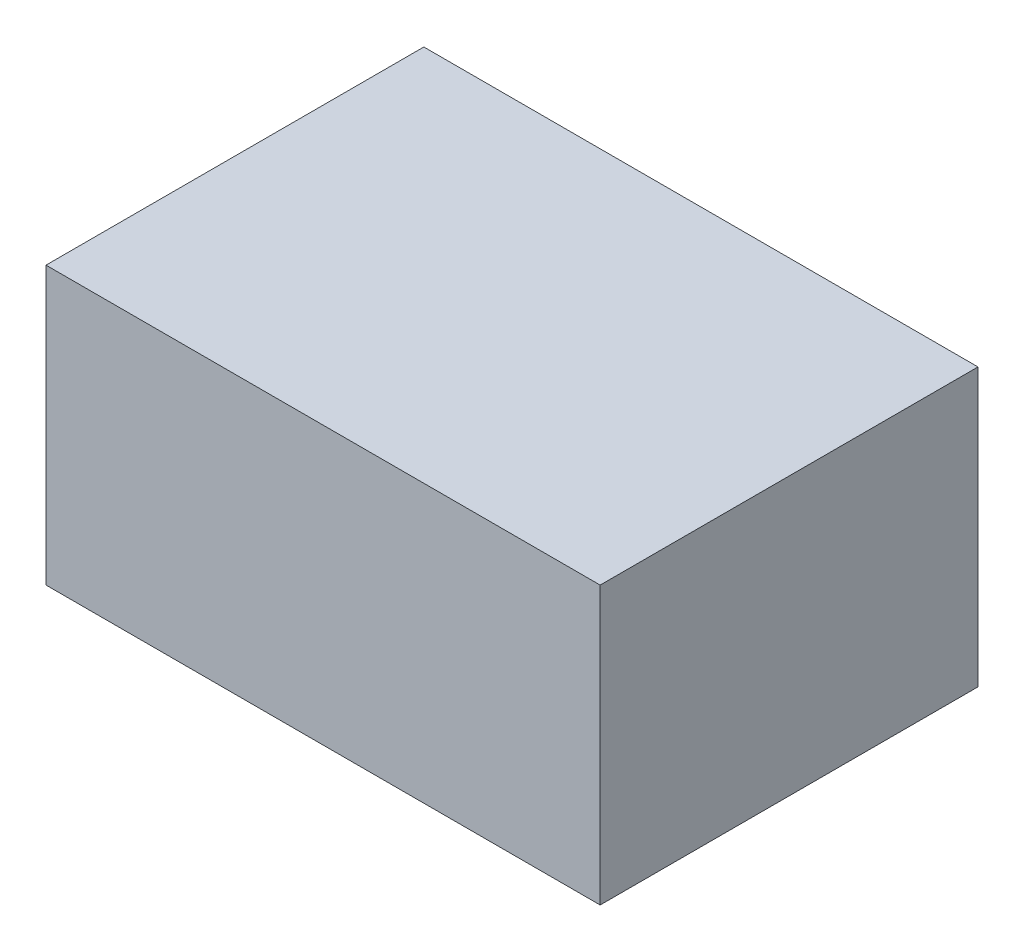
SolidWorks part; units mm, degrees
ref_plane "Front Plane" through (0, 0, 0) normal (0, 0, 1) x (1, 0, 0)
ref_plane "Top Plane" through (0, 0, 0) normal (0, 1, 0) x (1, 0, 0)
ref_plane "Right Plane" through (0, 0, 0) normal (1, 0, 0) x (0, 0, -1)
sketch "Sketch1" plane through (0, 0, 0) normal (0, 0, 1) x (1, 0, 0)
  line L1 (0, 0) -> (279.4, 0)
  line L2 (0, 0) -> (0, 139.7)
  line L3 (0, 139.7) -> (279.4, 139.7)
  line L4 (279.4, 0) -> (279.4, 139.7)
  dimension "D1" = 279.4
  dimension "D2" = 139.7
extrude "Boss-Extrude1" add sketch "Sketch1" along normal blind 190.5
